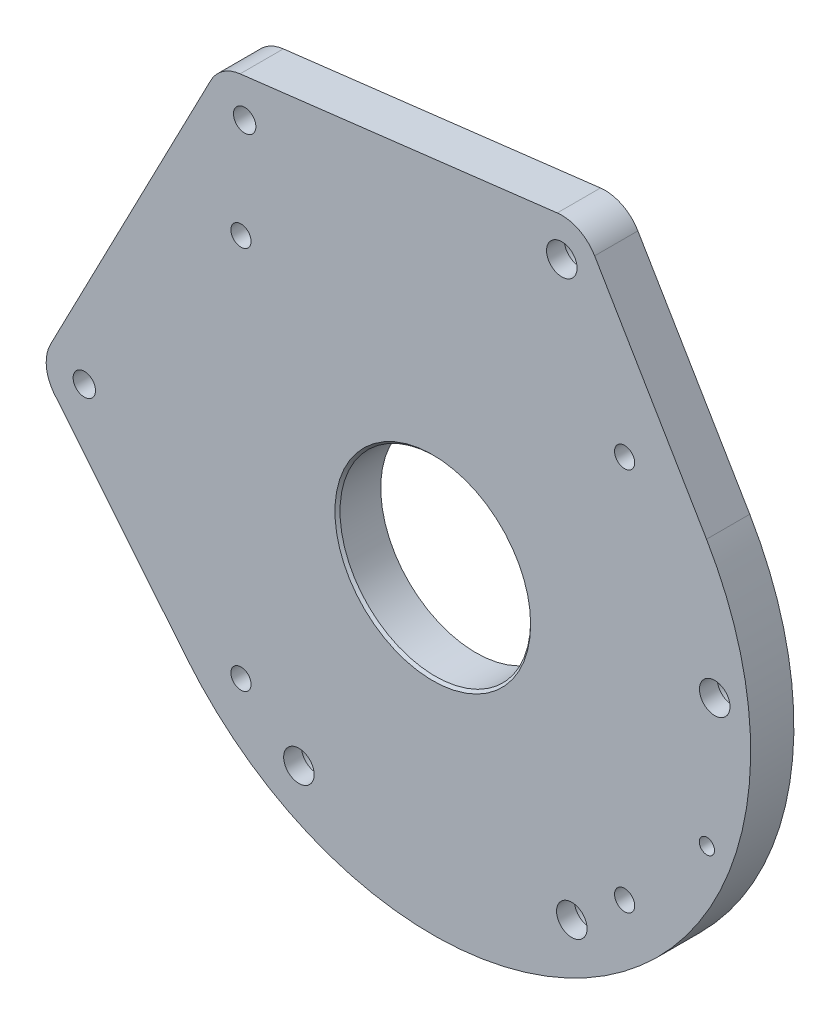
SolidWorks part; units mm, degrees
ref_plane "Front Plane" through (0, 0, 0) normal (0, 0, 1) x (1, 0, 0)
ref_plane "Top Plane" through (0, 0, 0) normal (0, 1, 0) x (1, 0, 0)
ref_plane "Right Plane" through (0, 0, 0) normal (1, 0, 0) x (0, 0, -1)
sketch "Sketch1" plane through (0, 0, 0) normal (0, 0, 1) x (1, 0, 0)
  line L0 (-73.98, 115.44) -> (50.73, 130.43) construction
  line L1 (50.73, 130.43) -> (110.87, 11.1) construction
  line L2 (110.87, 11.1) -> (107.78, -40.88) construction
  line L3 (107.78, -40.88) -> (54.67, -92.57) construction
  line L4 (54.67, -92.57) -> (-52.65, -93.77) construction
  line L5 (-52.65, -93.77) -> (-137.03, -5.99) construction
  line L6 (-137.03, -5.99) -> (-73.98, 115.44) construction
  line L12 (-147.844, -16.3851) -> (-96.9398, -78.9157)
  line L15 (-0.6436, 145.4272) -> (0.4814, -108.7728) construction
  line L17 (-150.3424, 0.9222) -> (-87.2924, 122.3522)
  line L19 (-75.7701, 130.3328) -> (48.9399, 145.3228)
  line L20 (63.6464, 138.0567) -> (107.6367, 63.5559)
  circle A0 centre (0, 0) radius 37.475
  circle A1 centre (-73.98, 115.44) radius 4
  circle A2 centre (50.73, 130.43) radius 6
  circle A3 centre (110.87, 11.1) radius 6
  circle A4 centre (107.78, -40.88) radius 1.6879
  circle A5 centre (54.67, -92.57) radius 6
  circle A6 centre (-52.65, -93.77) radius 6
  circle A7 centre (-137.03, -5.99) radius 4
  arc A10 (-150.3424, 0.9222) -> (-147.844, -16.3851) centre (-137.03, -5.99) ccw
  arc A24 (-96.9398, -78.9157) -> (107.6367, 63.5559) centre (0, 0) ccw
  arc A27 (-75.7701, 130.3328) -> (-87.2924, 122.3522) centre (-73.98, 115.44) ccw
  arc A28 (63.6464, 138.0567) -> (48.9399, 145.3228) centre (50.73, 130.43) ccw
  dimension "D1" = 50.73
  dimension "D15" = 12
  dimension "D16" = 8
  dimension "D17" = 74.95
  dimension "D18" = 15
  dimension "D24" = 250
  dimension "D2" = 73.98
  dimension "D3" = 137.03
  dimension "D4" = 52.65
  dimension "D5" = 54.67
  dimension "D6" = 107.78
  dimension "D7" = 110.87
  dimension "D8" = 11.1
  dimension "D9" = 130.43
  dimension "D10" = 115.44
  dimension "D11" = 5.99
  dimension "D12" = 93.77
  dimension "D13" = 92.57
  dimension "D14" = 40.88
extrude "Boss-Extrude1" add sketch "Sketch1" along normal blind 17
sketch "Sketch2" plane through (0, 0, 17) normal (0, 0, 1) x (1, 0, 0)
  line L0 (0, 0) -> (0, 106.68) construction
  line L1 (0, 0) -> (-106.68, 0) construction
  line L2 (-75.4342, 75.4342) -> (0, 0) construction
  circle A0 centre (0, 0) radius 106.68 construction
  circle A1 centre (-75.4342, 75.4342) radius 4.1383
  circle A2 centre (75.4342, 75.4342) radius 4.1383
  circle A3 centre (75.4342, -75.4342) radius 4.1383
  circle A4 centre (-75.4342, -75.4342) radius 4.1383
  circle A5 centre (0, 0) radius 125 construction
  point P16 (0, 0)
  point P25 (0, 0)
  dimension "D1" = 213.36
  dimension "D3" = 45
  dimension "D4" = 250
  dimension "D2" = 4
hole_wizard "M10x1.25 Tapped Hole1" positions "3DSketch1" profile "Sketch4" tap size "M10x1.25" standard "ANSI Metric" end condition through all
sketch3d "3DSketch1"
  line L0 (-73.98, 115.44, 17) -> (-73.98, 115.44, 0) construction
  line L1 (-137.03, -5.99, 17) -> (-137.03, -5.99, 0) construction
  point P0 (-73.98, 115.44, 17)
  point P4 (-137.03, -5.99, 0)
sketch "Sketch4" plane through (-73.98, 115.44, 17) normal (1, 0, 0) x (0, -1, 0)
  line L0 (0, 0) -> (0, 17)
  line L1 (0, 17) -> (4.4, 17)
  line L2 (4.4, 17) -> (4.4, 0)
  line L5 (4.4, 0) -> (0, 0)
  line L11 (0, -6.35) -> (0, 107.95) construction
  dimension "Thru Tap Drill Dia." = 8.8
  dimension "Thru Tap Drill Depth" = 17
cosmetic thread "Hole Thread7" parameters "D2"=10
cosmetic thread "Hole Thread8" parameters "D2"=10
hole_wizard "Ø6.0mm Dowel Hole1" positions "3DSketch5" profile "Sketch8" hole size "Ø6.0" standard "ANSI Metric" end condition through all
sketch3d "3DSketch5"
  line L0 (107.78, -40.88, 17) -> (107.78, -40.88, 0) construction
  point P0 (107.78, -40.88, 17)
sketch "Sketch8" plane through (107.78, -40.88, 17) normal (1, 0, 0) x (0, -1, 0)
  line L0 (0, 0) -> (0, 17)
  line L1 (0, 17) -> (3, 17)
  line L2 (3, 17) -> (3, 0)
  line L5 (3, 0) -> (0, 0)
  line L11 (0, -6.35) -> (0, 107.95) construction
  dimension "Thru Hole Dia." = 6
  dimension "Thru Hole Depth" = 17
hole_wizard "3/8-16 Tapped Hole1" positions "3DSketch6" profile "Sketch9" tap size "3/8-16" standard "ANSI Inch" end condition through all
sketch3d "3DSketch6"
  point P0 (-75.4342, 75.4342, 17)
  point P3 (-75.4342, -75.4342, 17)
  point P6 (75.4342, -75.4342, 17)
  point P9 (75.4342, 75.4342, 17)
sketch "Sketch9" plane through (-75.4342, 75.4342, 17) normal (1, 0, 0) x (0, -1, 0)
  line L0 (0, 0) -> (0, 17)
  line L1 (0, 17) -> (3.9687, 17)
  line L2 (3.9687, 17) -> (3.9687, 0)
  line L5 (3.9687, 0) -> (0, 0)
  line L11 (0, -6.35) -> (0, 107.95) construction
  dimension "Thru Tap Drill Dia." = 7.9375
  dimension "Thru Tap Drill Depth" = 17
cosmetic thread "Hole Thread3" parameters "D2"=9.525
cosmetic thread "Hole Thread4" parameters "D2"=9.525
cosmetic thread "Hole Thread5" parameters "D2"=9.525
cosmetic thread "Hole Thread6" parameters "D2"=9.525
chamfer "Chamfer1" distance 1 angle 45 1 edges at (37.475, 0, 17)
hole_wizard "CBORE for M10 SHCS1" positions "3DSketch9" profile "Sketch12" counterbore size "M10" standard "ANSI Metric" end condition through all
sketch3d "3DSketch9"
  line L0 (50.73, 130.43, 17) -> (50.73, 130.43, 0) construction
  line L1 (110.87, 11.1, 17) -> (110.87, 11.1, 0) construction
  line L2 (54.67, -92.57, 17) -> (54.67, -92.57, 0) construction
  line L3 (-52.65, -93.77, 17) -> (-52.65, -93.77, 0) construction
  point P0 (50.73, 130.43, 0)
  point P4 (110.87, 11.1, 0)
  point P8 (54.67, -92.57, 0)
  point P12 (-52.65, -93.77, 0)
sketch "Sketch12" plane through (50.73, 130.43, 0) normal (1, 0, 0) x (0, 1, 0)
  line L0 (0, 0) -> (0, 17)
  line L1 (0, 17) -> (5.25, 17)
  line L3 (5.25, 17) -> (5.25, 10)
  line L4 (9, 10) -> (5.25, 10)
  line L5 (9, 10) -> (9, 0.025)
  line L6 (9, 0.025) -> (9.025, 0)
  line L7 (9.025, 0) -> (0, 0)
  line L8 (-9, 0.025) -> (-9.025, 0) construction
  line L11 (0, -6.35) -> (0, 107.95) construction
  dimension "Thru Hole Dia." = 10.5
  dimension "Thru Hole Depth" = 17
  dimension "C'Bore Dia." = 18
  dimension "C'Bore Depth" = 10
  dimension "Near C'Sink Dia." = 18.05
  dimension "Near C'Sink Angle" = 90
